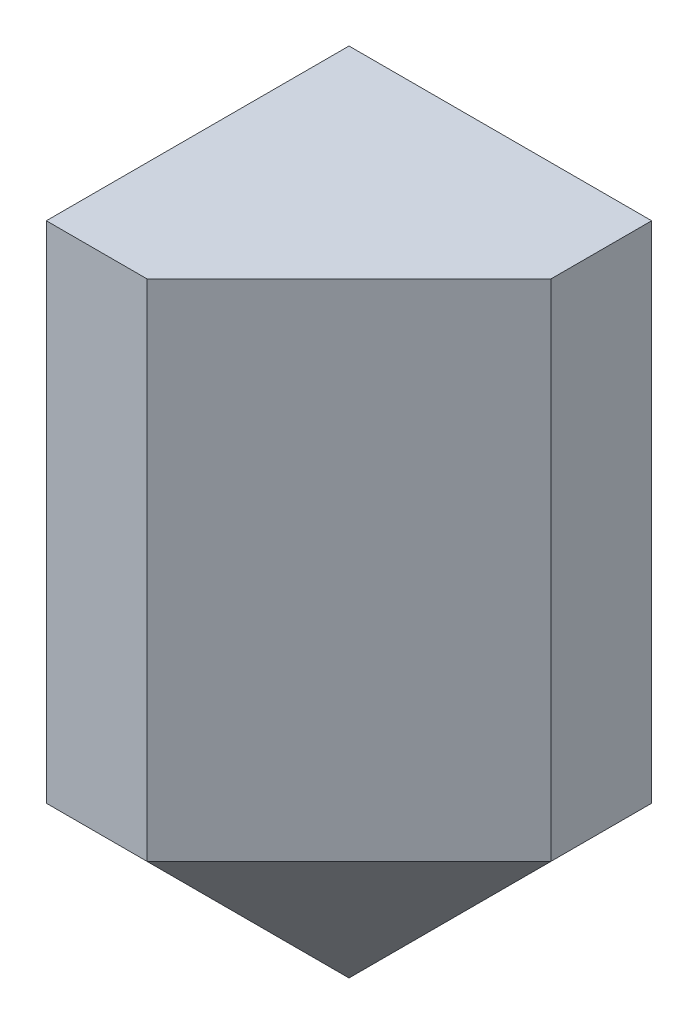
SolidWorks part; units mm, degrees
material "ABS"
ref_plane "Piano frontale" through (0, 0, 0) normal (0, 0, 1) x (1, 0, 0)
ref_plane "Piano superiore" through (0, 0, 0) normal (0, 1, 0) x (1, 0, 0)
ref_plane "Piano destro" through (0, 0, 0) normal (1, 0, 0) x (0, 0, -1)
sketch "Schizzo1" plane through (0, 0, 0) normal (0, 0, 1) x (1, 0, 0)
  line L1 (0, 0) -> (30, 0)
  line L2 (0, 0) -> (0, 40)
  line L3 (0, 40) -> (30, 40)
  line L4 (30, 0) -> (30, 40)
  dimension "D1" = 30
  dimension "D2" = 40
extrude "Estrusione-Estrusione1" add sketch "Schizzo1" along normal blind 30
chamfer "Smusso1" distance 20 angle 45 3 edges at (30, 20, 30) (30, 0, 15) (15, 0, 30)
sketch "Schizzo2" plane through (0, 40, 0) normal (0, 1, 0) x (1, 0, 0)
  line L0 (0, 0) -> (30, 0)
  line L1 (30, 0) -> (30, -10)
  line L2 (30, -10) -> (10, -30)
  line L3 (10, -30) -> (0, -30)
  line L4 (0, -30) -> (0, 0)
extrude "Estrusione-Estrusione2" add sketch "Schizzo2" along normal blind 30
hole_wizard "Foro per Vite M5-1" positions "Schizzo3" profile "Schizzo4" hole size "M5" standard "ISO"
sketch "Schizzo3" plane through (0, 0, 0) normal (-1, 0, 0) x (0, 0, 1)
  line L0 (18, 20) -> (18, 34) construction
  line L2 (0, 70) -> (0, 0) construction
  line L4 (18, 48) -> (18, 34) construction
  line L5 (0, 70) -> (30, 70) construction
  point P0 (18, 20)
  point P28 (18, 48)
  dimension "D1" = 18
  dimension "D2" = 22
  dimension "D3" = 14
  dimension "D4" = 14
sketch "Schizzo4" plane through (0, 20, 18) normal (0, 1, 0) x (0, 0, 1)
  line L0 (0, 0) -> (0, 14.6524)
  line L1 (0, 14.6524) -> (2.75, 13)
  line L2 (2.75, 13) -> (2.75, 0)
  line L5 (2.75, 0) -> (0, 0)
  line L10 (0, 14.6524) -> (-2.75, 13) construction
  line L11 (0, -6.35) -> (0, 107.95) construction
  dimension "Hole Dia." = 5.5
  dimension "Hole Depth" = 13
  dimension "Drill Angle" = 118
hole_wizard "Foro per Vite M5-2" positions "Schizzo3D1" profile "Schizzo5" hole size "M5" standard "ISO"
sketch3d "Schizzo3D1"
  line L4 (30, 70, 0) -> (0, 70, 0) construction
  line L5 (0, 70, 0) -> (0, 0, 0) construction
  point P2 (18, 20, 0)
  dimension "D1" = 50
  dimension "D2" = 18
sketch "Schizzo5" plane through (18, 20, 0) normal (1, 0, 0) x (0, 1, 0)
  line L0 (0, 0) -> (0, 14.6524)
  line L1 (0, 14.6524) -> (2.75, 13)
  line L2 (2.75, 13) -> (2.75, 0)
  line L5 (2.75, 0) -> (0, 0)
  line L10 (0, 14.6524) -> (-2.75, 13) construction
  line L11 (0, -6.35) -> (0, 107.95) construction
  dimension "Hole Dia." = 5.5
  dimension "Hole Depth" = 13
  dimension "Drill Angle" = 118
sketch "Schizzo6" plane through (0, 0, 0) normal (0, 0, -1) x (-1, 0, 0)
  line L0 (-30, 20) -> (-30, 70) construction
  line L1 (-30, 70) -> (0, 70) construction
  circle A0 centre (-15, 55) radius 7.5
  dimension "D1" = 15
  dimension "D3" = 15
  dimension "D2" = 15
extrude "Taglio-Estrusione1" cut sketch "Schizzo6" against normal blind 3
sketch "Schizzo7" plane through (0, 0, 3) normal (0, 0, -1) x (-1, 0, 0)
  point P0 (-15, 55)
hole_wizard "Foro per Vite M4-1" positions "Schizzo7" profile "Schizzo8" hole size "M4" standard "ISO"
sketch "Schizzo8" plane through (15, 55, 3) normal (1, 0, 0) x (0, 1, 0)
  line L0 (0, 0) -> (0, 11.3519)
  line L1 (0, 11.3519) -> (2.25, 10)
  line L2 (2.25, 10) -> (2.25, 0)
  line L5 (2.25, 0) -> (0, 0)
  line L10 (0, 11.3519) -> (-2.25, 10) construction
  line L11 (0, -6.35) -> (0, 107.95) construction
  dimension "Hole Dia." = 4.5
  dimension "Hole Depth" = 10
  dimension "Drill Angle" = 118
